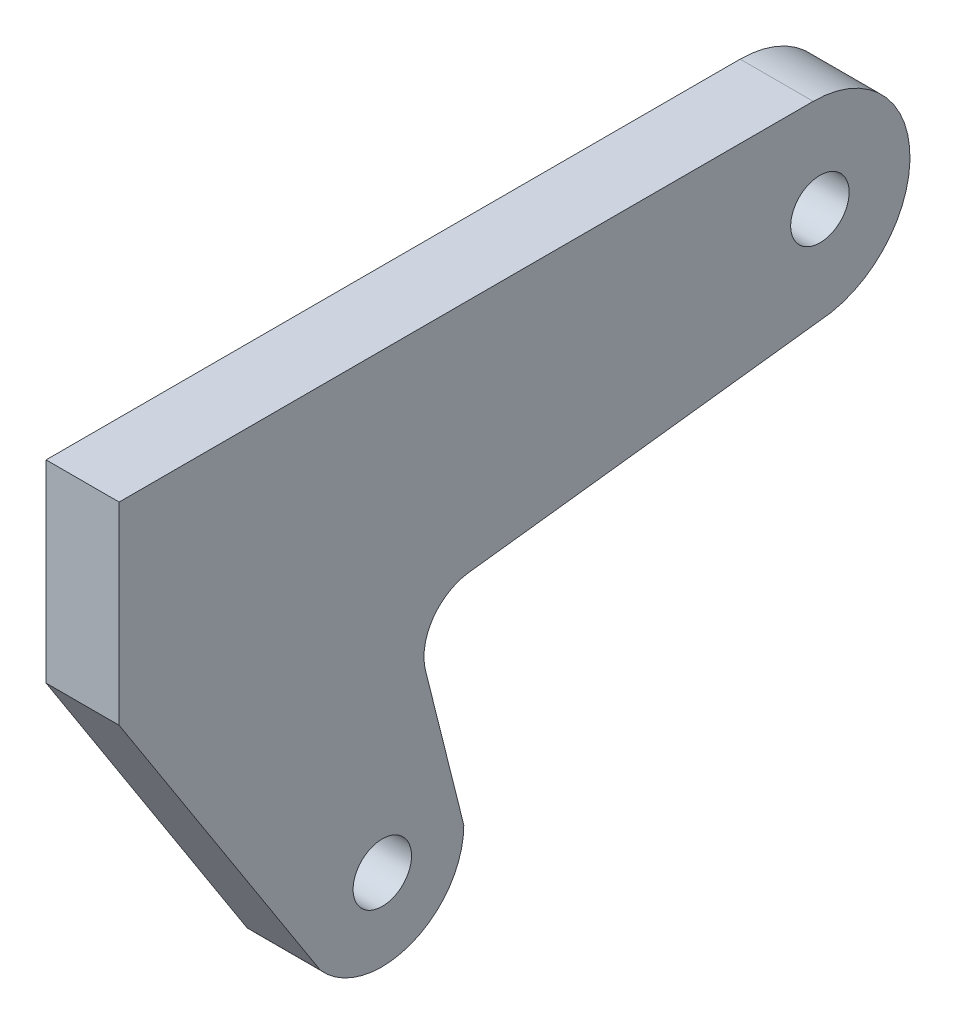
SolidWorks part; units mm, degrees
ref_plane "Спереди" through (0, 0, 0) normal (0, 0, 1) x (1, 0, 0)
ref_plane "Сверху" through (0, 0, 0) normal (0, 1, 0) x (1, 0, 0)
ref_plane "Справа" through (0, 0, 0) normal (1, 0, 0) x (0, 0, -1)
sketch "Эскиз1" plane through (0, 0, 0) normal (1, 0, 0) x (0, 0, -1)
  line L0 (0, 0) -> (0, -26.4575)
  line L1 (0, 0) -> (94.9883, 0)
  line L2 (0, -26.4575) -> (27.5204, -69.2327)
  line L3 (41.9253, -40.9216) -> (47.1682, -61.8708)
  line L4 (0, -33.2288) -> (45, -33.2288) construction
  line L7 (69.881, -13.2288) -> (91.6872, -13.2288) construction
  line L9 (95.7801, -26.4575) -> (47.8723, -32.2731)
  arc A0 (27.5204, -69.2327) -> (47.1682, -61.8708) centre (35.9651, -61.8708) ccw
  arc A1 (94.9883, 0) -> (95.7801, -26.4575) centre (94.9883, -13.2406) cw
  arc A2 (47.8723, -32.2731) -> (41.9253, -40.9216) centre (48.7158, -39.2221) ccw
  point P16 (40, -33.2288)
  dimension "D1" = 7
extrude "Вытянуть1" add sketch "Эскиз1" along normal blind 10
sketch "Эскиз2" plane through (10, 0, 0) normal (1, 0, 0) x (0, 0, -1)
  line L0 (69.881, -13.2288) -> (130.5947, -13.2288) construction
  circle A0 centre (95.9044, -13.2288) radius 4
  circle A1 centre (36.0154, -61.9267) radius 4
extrude "Вырез-Вытянуть1" cut sketch "Эскиз2" against normal through all
